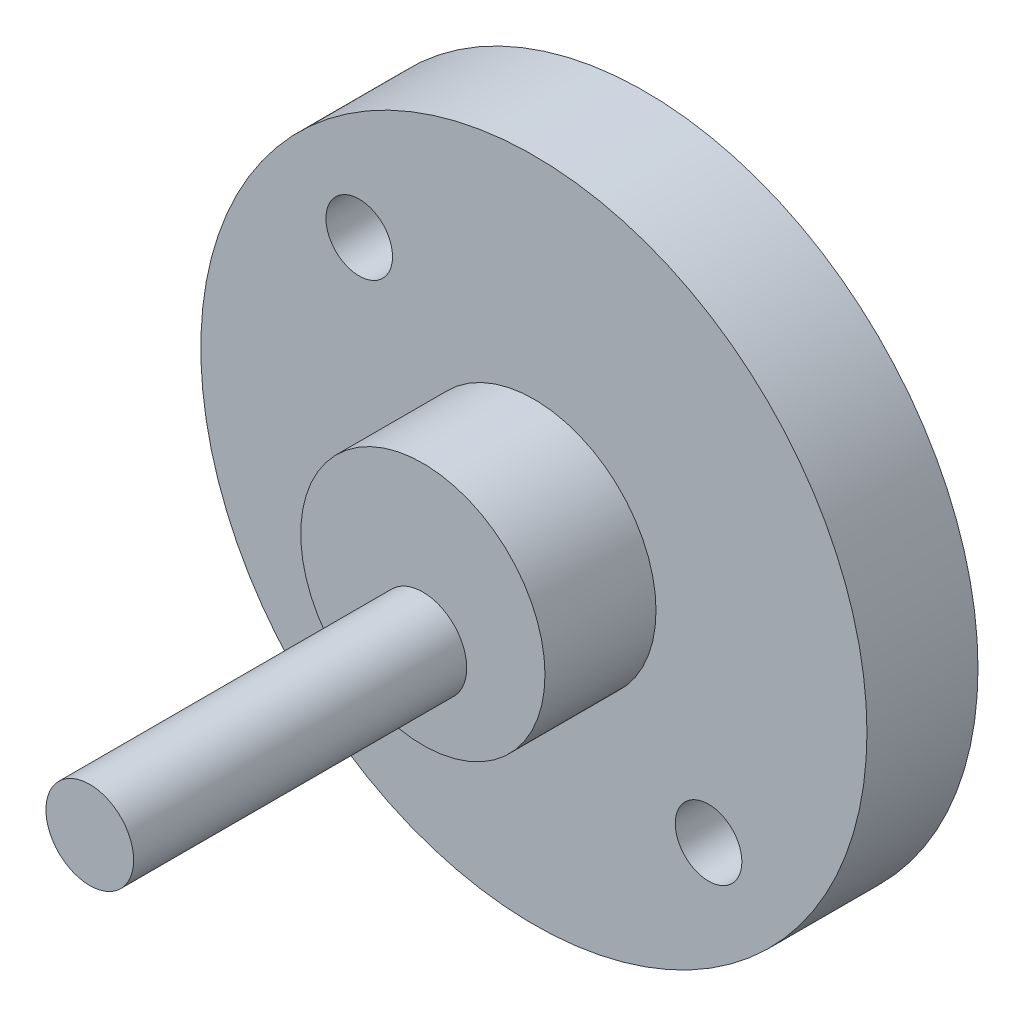
SolidWorks part; units mm, degrees
material "ABS"
ref_plane "Front Plane" through (0, 0, 0) normal (0, 0, 1) x (1, 0, 0)
ref_plane "Top Plane" through (0, 0, 0) normal (0, 1, 0) x (1, 0, 0)
ref_plane "Right Plane" through (0, 0, 0) normal (1, 0, 0) x (0, 0, -1)
sketch "Sketch1" plane through (0, 0, 0) normal (0, 0, 1) x (1, 0, 0)
  circle A0 centre (0, 0) radius 30
  dimension "D1" = 60
extrude "Boss-Extrude1" add sketch "Sketch1" along normal blind 10 contours A0
sketch "Sketch2" plane through (0, 0, 10) normal (0, 0, 1) x (1, 0, 0)
  circle A0 centre (0, 0) radius 11
  dimension "D1" = 22
sketch "Sketch5" plane through (0, 0, 10) normal (0, 0, 1) x (1, 0, 0)
  line L0 (0, 0) -> (0, 66.1073) construction
  line L1 (-5.7455, 0) -> (-60.7604, 0) construction
  line L2 (0, 0) -> (-38.8576, 38.8576) construction
  circle A0 centre (0, 0) radius 22.25 construction
  point P8 (-15.7331, 15.7331)
  point P10 (15.7331, -15.7331)
  point P15 (-15.7331, -15.7331)
  dimension "D1" = 45
hole_wizard "Ø6.0mm Dowel Hole1" positions "Sketch7" profile "Sketch6" hole size "Ø6.0" standard "ANSI Metric" end condition up to next
sketch "Sketch7" plane through (0, 0, 10) normal (0, 0, 1) x (1, 0, 0)
  point P0 (-15.7331, 15.7331)
  point P3 (15.7331, -15.7331)
  point P6 (-15.7331, -15.7331)
sketch "Sketch6" plane through (-15.7331, 15.7331, 10) normal (1, 0, 0) x (0, -1, 0)
  line L0 (0, 0) -> (0, 10)
  line L1 (0, 10) -> (3, 10)
  line L2 (3, 10) -> (3, 0)
  line L5 (3, 0) -> (0, 0)
  line L11 (0, -6.35) -> (0, 107.95) construction
  dimension "Thru Hole Dia." = 6
  dimension "Thru Hole Depth" = 10
extrude "Boss-Extrude2" add sketch "Sketch2" along normal blind 10
sketch "Sketch9" plane through (0, 0, 20) normal (0, 0, 1) x (1, 0, 0)
  line L2 (0, -200000) -> (0, 200066.1073) construction
  circle A0 centre (0, -3) radius 3.95
  point P0 (0, -3)
  dimension "D2" = 7.9
  dimension "D1" = 3
extrude "Boss-Extrude3" add sketch "Sketch9" along normal blind 30
